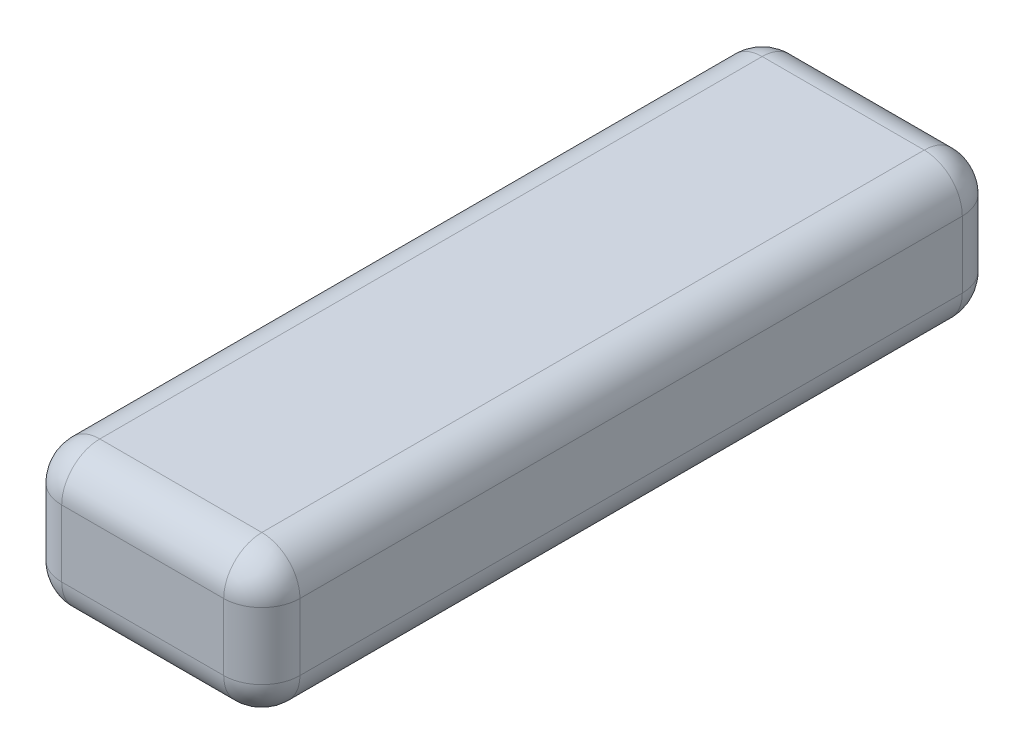
SolidWorks part; units mm, degrees
ref_plane "Plan de face" through (0, 0, 0) normal (0, 0, 1) x (1, 0, 0)
ref_plane "Plan de dessus" through (0, 0, 0) normal (0, 1, 0) x (1, 0, 0)
ref_plane "Plan de droite" through (0, 0, 0) normal (1, 0, 0) x (0, 0, -1)
sketch "Esquisse1" plane through (0, 0, 0) normal (0, 0, 1) x (1, 0, 0)
  line L0 (-25, 15) -> (25, -15) construction
  line L1 (-25, 15) -> (25, 15)
  line L2 (-25, 15) -> (-25, -15)
  line L3 (-25, -15) -> (25, -15)
  line L4 (25, 15) -> (25, -15)
  dimension "D1" = 50
  dimension "D2" = 30
extrude "Boss.-Extru.1" add sketch "Esquisse1" along normal blind 155
fillet "Congé1" radius 8 12 edges at (-25, -15, 77.5) (0, -15, 155) (25, -15, 77.5) (0, -15, 0) (-25, 0, 0) (25, 0, 0) (0, 15, 0) (-25, 15, 77.5) (25, 0, 155) (25, 15, 77.5) (0, 15, 155) (-25, 0, 155)
